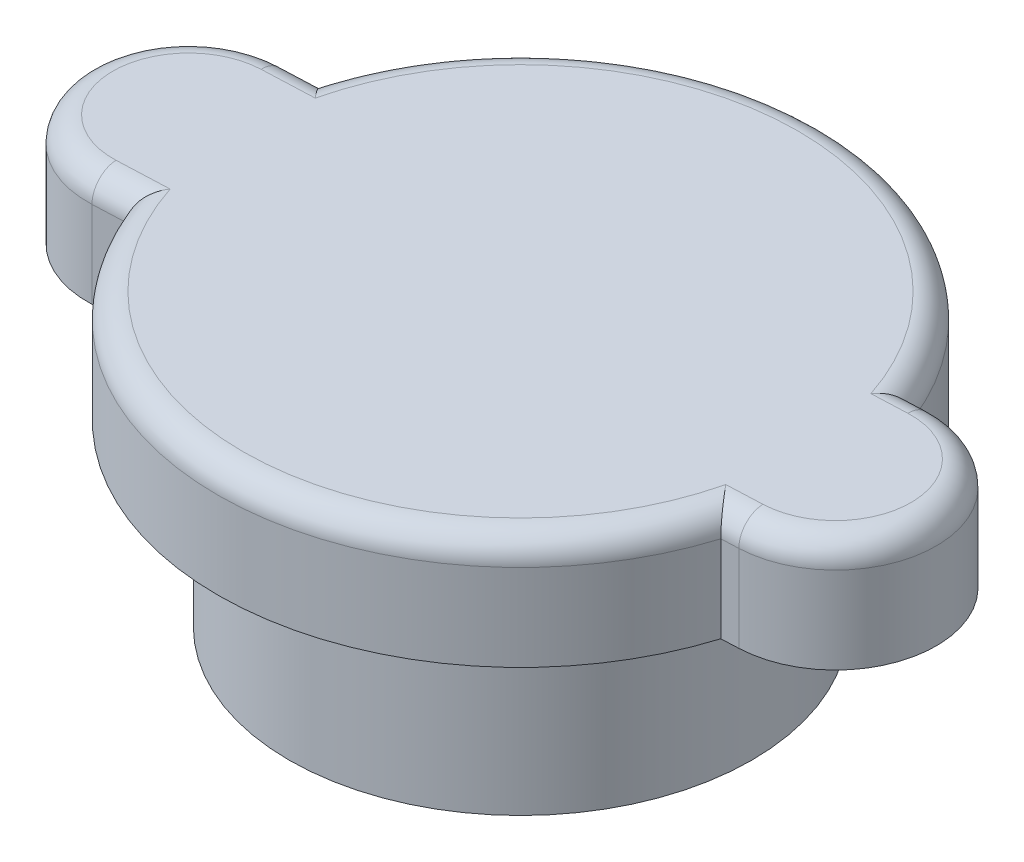
SolidWorks part; units mm, degrees
ref_plane "Front Plane" through (0, 0, 0) normal (0, 0, 1) x (1, 0, 0)
ref_plane "Top Plane" through (0, 0, 0) normal (0, 1, 0) x (1, 0, 0)
ref_plane "Right Plane" through (0, 0, 0) normal (1, 0, 0) x (0, 0, -1)
sketch "Sketch1" plane through (0, 0, 0) normal (0, 1, 0) x (1, 0, 0)
  line L0 (0, 0) -> (-25.3787, -1.0412)
  circle A0 centre (0, 0) radius 25.4
  circle A1 centre (0, 0) radius 23.4
  point P4 (-14.9799, -20.5125)
  dimension "D1" = 50.8
  dimension "D2" = 46.8
sketch "Sketch11" plane through (0, 0, 0) normal (0, 1, 0) x (1, 0, 0)
  circle A0 centre (0, 0) radius 18.415
  dimension "D1" = 36.83
extrude "neck" add sketch "Sketch11" along normal blind 14.224
sketch "Sketch12" plane through (0, 14.224, 0) normal (0, 1, 0) x (1, 0, 0)
  line L0 (-25.3787, -1.0412) -> (24.0782, 0.9878) construction
  line L1 (-25.7077, 6.9784) -> (23.7492, 9.0074)
  line L2 (-25.0496, -9.0608) -> (24.4073, -7.0318)
  circle A0 centre (0, 0) radius 24.0985
  arc A1 (-25.7077, 6.9784) -> (-25.0496, -9.0608) centre (-25.3787, -1.0412) ccw
  arc A2 (24.4073, -7.0318) -> (23.7492, 9.0074) centre (24.0782, 0.9878) ccw
  circle A3 centre (0, 0) radius 25.4 construction
  point P6 (-0.6502, -0.0267)
extrude "lid" add sketch "Sketch12" along normal blind 8.89 contours A0 | L2 A2 L1 A1
fillet "Fillet3" radius 2 8 edges at (23.0619, 23.114, -8.9792) (32.0978, 23.114, -1.3168) (23.7199, 23.114, 7.06) (0.9878, 23.114, 24.0782) (-23.7121, 23.114, 9.0059) (-33.3982, 23.114, 1.3702) (-24.3701, 23.114, -7.0333) (-0.9878, 23.114, -24.0782)
equation "\"can_diameter\"= 2in"
equation "\"D1@can\" = \"can_thickness\""
equation "\"inlet_diameter\"=9.525"
